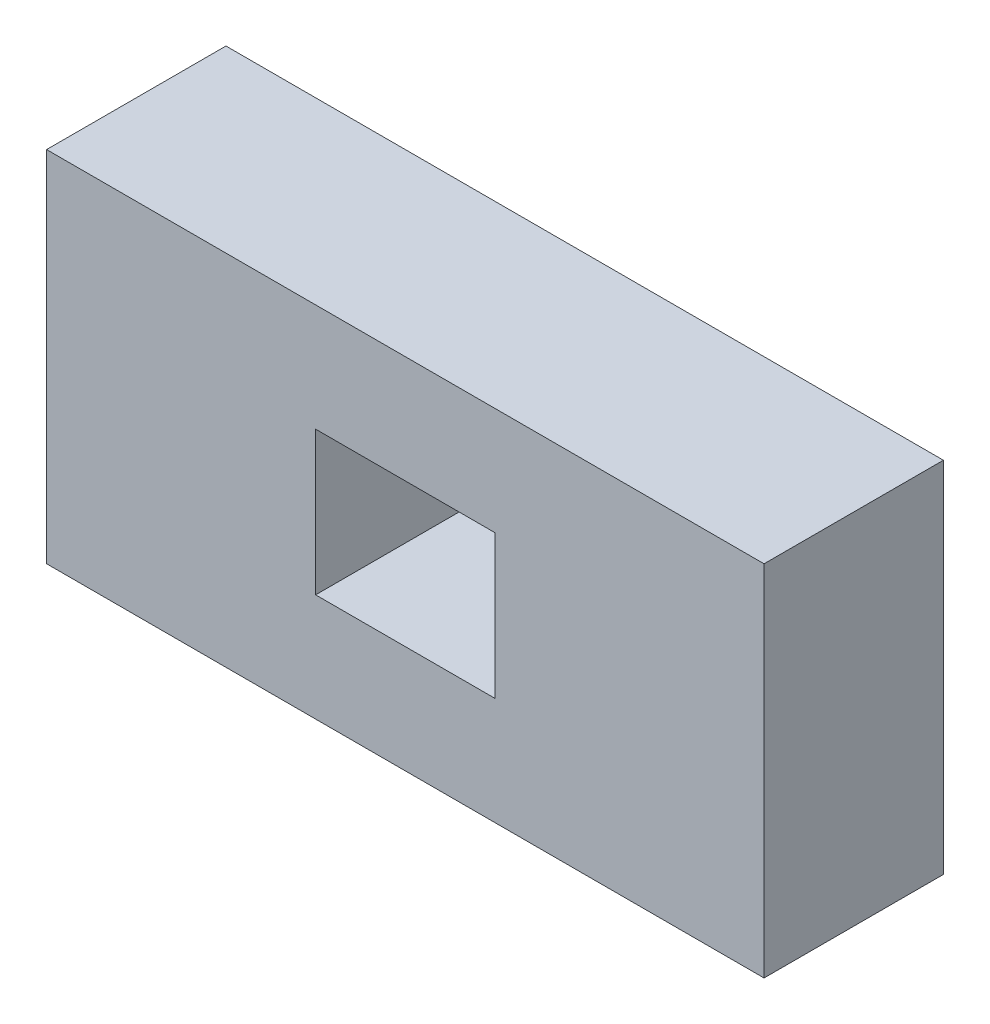
SolidWorks part; units mm, degrees
ref_plane "Front Plane" through (0, 0, 0) normal (0, 0, 1) x (1, 0, 0)
ref_plane "Top Plane" through (0, 0, 0) normal (0, 1, 0) x (1, 0, 0)
ref_plane "Right Plane" through (0, 0, 0) normal (1, 0, 0) x (0, 0, -1)
sketch "RectangleSketch" plane through (0, 0, 0) normal (0, 0, 1) x (1, 0, 0)
  line L1 (0, 0) -> (40, 0)
  line L2 (0, 0) -> (0, 20)
  line L3 (0, 20) -> (40, 20)
  line L4 (40, 0) -> (40, 20)
  dimension "width_mm" = 40
  dimension "height_mm" = 20
extrude "BlindBoss" add sketch "RectangleSketch" along normal blind 10 separate body
sketch "CutSketch" plane through (0, 0, 10) normal (0, 0, 1) x (1, 0, 0)
  line L1 (15, 6) -> (25, 6)
  line L2 (15, 6) -> (15, 14)
  line L3 (15, 14) -> (25, 14)
  line L4 (25, 6) -> (25, 14)
  dimension "cut_width_mm" = 10
  dimension "cut_height_mm" = 8
  dimension "cut_left_mm" = 15
  dimension "cut_bottom_mm" = 6
extrude "ThroughAllCut" cut sketch "CutSketch" against normal through all
equation "\"cut_left_mm@CutSketch\" = (\"width_mm@RectangleSketch\" - \"cut_width_mm@CutSketch\") / 2"
equation "\"cut_bottom_mm@CutSketch\" = (\"height_mm@RectangleSketch\" - \"cut_height_mm@CutSketch\") / 2"
